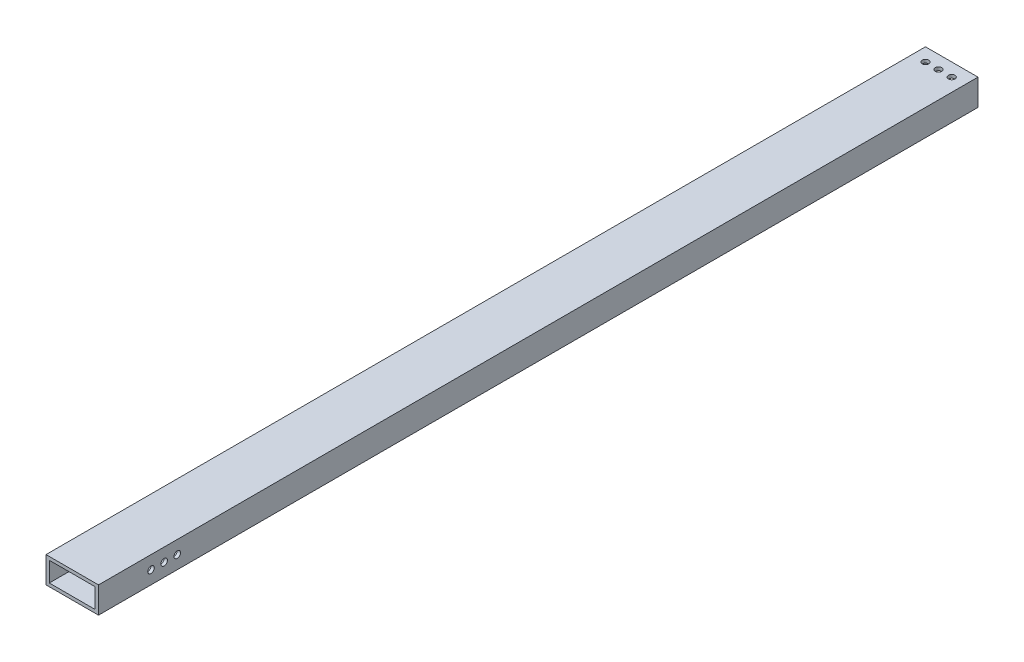
SolidWorks part; units mm, degrees
ref_plane "Front Plane" through (0, 0, 0) normal (0, 0, 1) x (1, 0, 0)
ref_plane "Top Plane" through (0, 0, 0) normal (0, 1, 0) x (1, 0, 0)
ref_plane "Right Plane" through (0, 0, 0) normal (1, 0, 0) x (0, 0, -1)
sketch "Sketch1" plane through (0, 0, 0) normal (0, 0, 1) x (1, 0, 0)
  line L0 (3.175, 22.225) -> (47.625, 22.225)
  line L1 (0, 0) -> (50.8, 0)
  line L2 (0, 0) -> (0, 25.4)
  line L3 (0, 25.4) -> (50.8, 25.4)
  line L4 (50.8, 0) -> (50.8, 25.4)
  line L5 (47.625, 3.175) -> (47.625, 22.225)
  line L6 (3.175, 3.175) -> (47.625, 3.175)
  line L7 (3.175, 3.175) -> (3.175, 22.225)
  dimension "D1" = 50.8
  dimension "D2" = 25.4
  dimension "D3" = 3.175
extrude "Boss-Extrude1" add sketch "Sketch1" along normal blind 850.9
sketch "Sketch2" plane through (50.8, 0, 0) normal (1, 0, 0) x (0, 0, -1)
  line L0 (-800.1, 12.7) -> (-850.9, 12.7) construction
  line L1 (-850.9, 0) -> (-850.9, 25.4) construction
  circle A0 centre (-800.1, 12.7) radius 3.175
  circle A1 centre (-787.4, 12.7) radius 3.175
  circle A2 centre (-774.7, 12.7) radius 3.175
  dimension "D2" = 6.35
  dimension "D1" = 50.8
  dimension "D4" = 12.7
  dimension "D3" = 3
extrude "Cut-Extrude1" cut sketch "Sketch2" against normal through all both and the other way through all
hole_wizard "1/4 (0.25) Diameter Hole3" positions "Sketch8" profile "Sketch9" hole size "1/4" standard "ANSI Inch" end condition through all
sketch "Sketch8" plane through (0, 25.4, 0) normal (0, 1, 0) x (1, 0, 0)
  line L0 (12.7, -12.7) -> (25.4, -12.7)
  line L1 (25.4, -12.7) -> (38.1, -12.7)
  line L3 (50.8, 0) -> (0, 0) construction
  line L4 (0, -850.9) -> (0, 0) construction
  point P0 (12.7, -12.7)
  point P2 (25.4, -12.7)
  point P4 (38.1, -12.7)
  dimension "D1" = 12.7
  dimension "0.5" = 12.7
  dimension "D2" = 12.7
sketch "Sketch9" plane through (12.7, 25.4, 12.7) normal (1, 0, 0) x (0, 0, 1)
  line L0 (0, 0) -> (0, 25.4)
  line L1 (0, 25.4) -> (3.175, 25.4)
  line L2 (3.175, 25.4) -> (3.175, 0)
  line L5 (3.175, 0) -> (0, 0)
  line L11 (0, -6.35) -> (0, 107.95) construction
  dimension "Thru Hole Dia." = 6.35
  dimension "Thru Hole Depth" = 25.4
